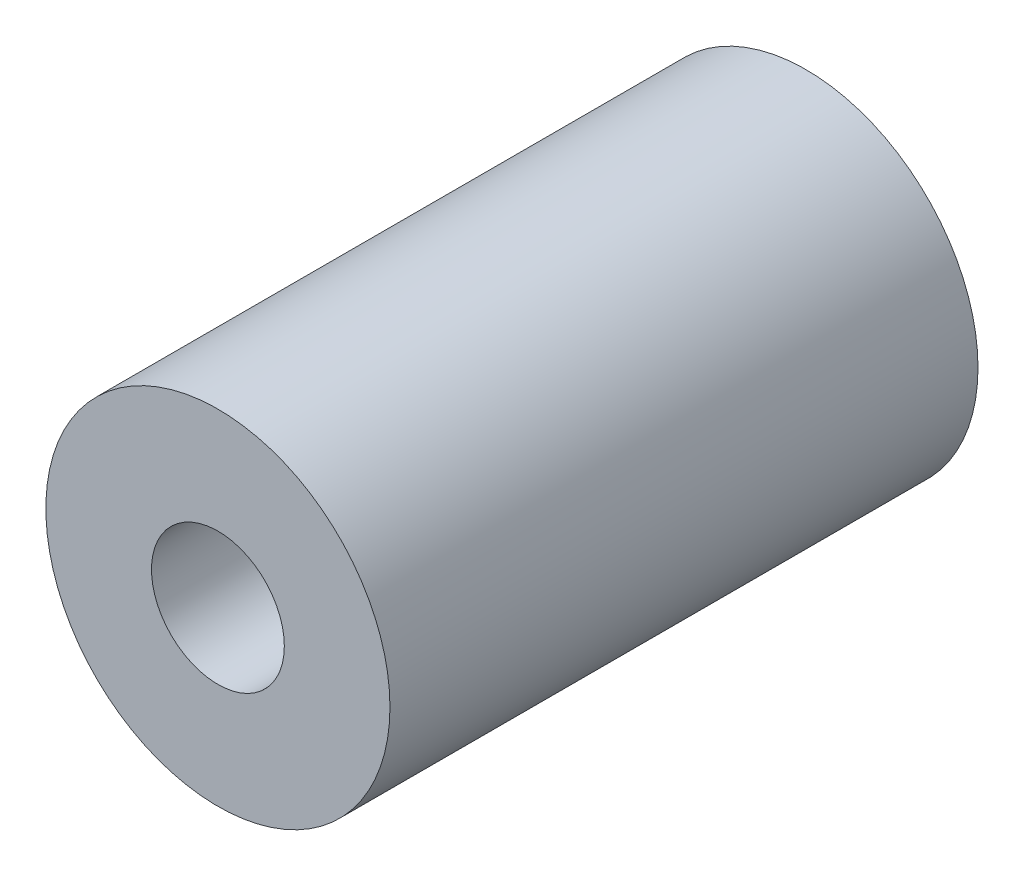
SolidWorks part; units mm, degrees
ref_plane "Front Plane" through (0, 0, 0) normal (0, 0, 1) x (1, 0, 0)
ref_plane "Top Plane" through (0, 0, 0) normal (0, 1, 0) x (1, 0, 0)
ref_plane "Right Plane" through (0, 0, 0) normal (1, 0, 0) x (0, 0, -1)
sketch "Sketch1" plane through (0, 0, 0) normal (0, 0, 1) x (1, 0, 0)
  circle A0 centre (0, 0) radius 3.95
  circle A1 centre (0, 0) radius 1.525
  dimension "D1" = 7.9
  dimension "D2" = 3.05
extrude "Boss-Extrude1" add sketch "Sketch1" along normal mid plane 13.5
